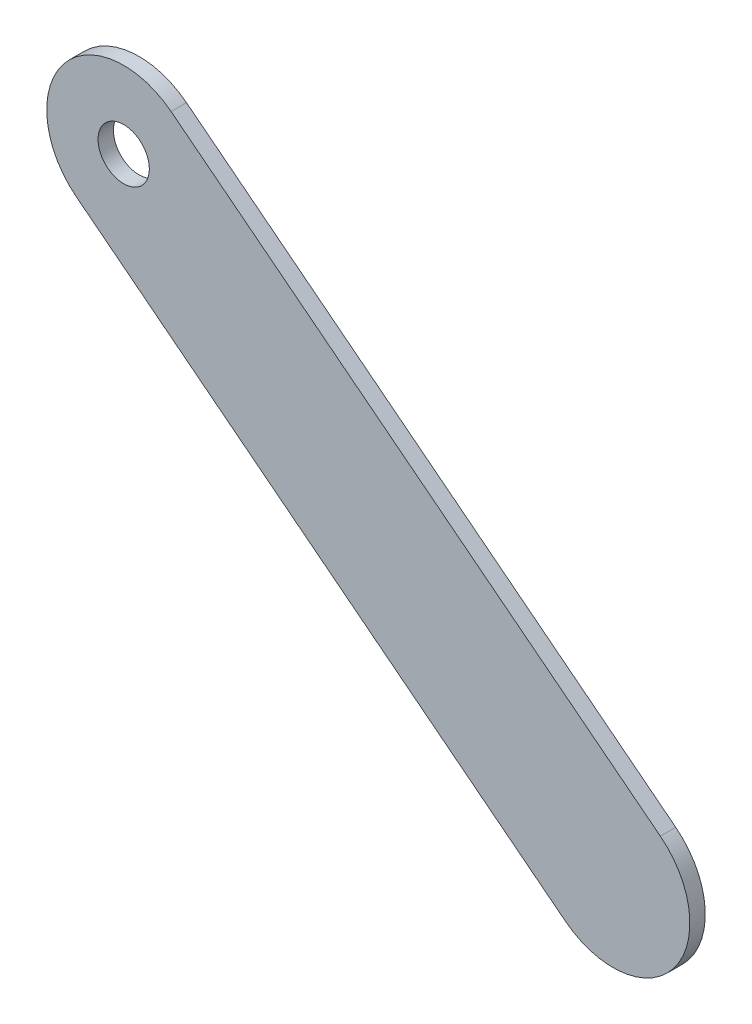
SolidWorks part; units mm, degrees
ref_plane "Front Plane" through (0, 0, 0) normal (0, 0, 1) x (1, 0, 0)
ref_plane "Top Plane" through (0, 0, 0) normal (0, 1, 0) x (1, 0, 0)
ref_plane "Right Plane" through (0, 0, 0) normal (1, 0, 0) x (0, 0, -1)
sketch "Sketch2" plane through (0, 0, 0) normal (0, 0, 1) x (1, 0, 0)
  point P0 (-95.3864, 74.6563)
sketch "Sketch1" plane through (0, 0, 0) normal (0, 0, 1) x (1, 0, 0)
  line L4 (-95.3864, 74.6563) -> (0, 0) construction
  line L5 (-86.1413, 86.4685) -> (9.2451, 11.8122)
  line L6 (-104.6315, 62.8441) -> (-9.2451, -11.8122)
  arc A4 (-86.1413, 86.4685) -> (-104.6315, 62.8441) centre (-95.3864, 74.6563) ccw
  arc A5 (-9.2451, -11.8122) -> (9.2451, 11.8122) centre (0, 0) ccw
  circle A6 centre (-95.3864, 74.6563) radius 5
  point P2 (-47.6932, 37.3282)
  dimension "D1" = 15
  dimension "D2" = 10
extrude "Boss-Extrude1" add sketch "Sketch1" along normal mid plane 3
